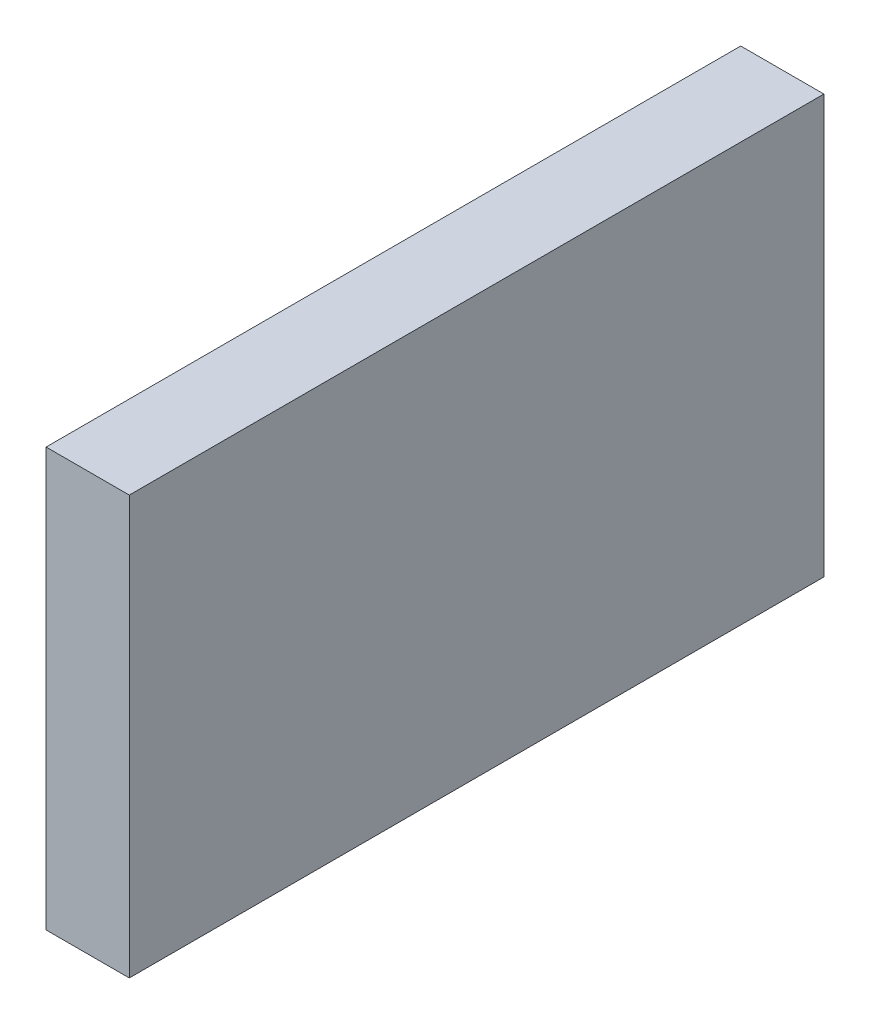
SolidWorks part; units mm, degrees
ref_plane "Front Plane" through (0, 0, 0) normal (0, 0, 1) x (1, 0, 0)
ref_plane "Top Plane" through (0, 0, 0) normal (0, 1, 0) x (1, 0, 0)
ref_plane "Right Plane" through (0, 0, 0) normal (1, 0, 0) x (0, 0, -1)
sketch "Sketch1" plane through (0, 0, 0) normal (1, 0, 0) x (0, 0, -1)
  line L1 (-54.8922, 34.6407) -> (28.6008, 34.6407)
  line L2 (-54.8922, 34.6407) -> (-54.8922, -15.6327)
  line L3 (-54.8922, -15.6327) -> (28.6008, -15.6327)
  line L4 (28.6008, 34.6407) -> (28.6008, -15.6327)
extrude "Boss-Extrude1" add sketch "Sketch1" along normal blind 10 contours L1 L4 L3 L2
